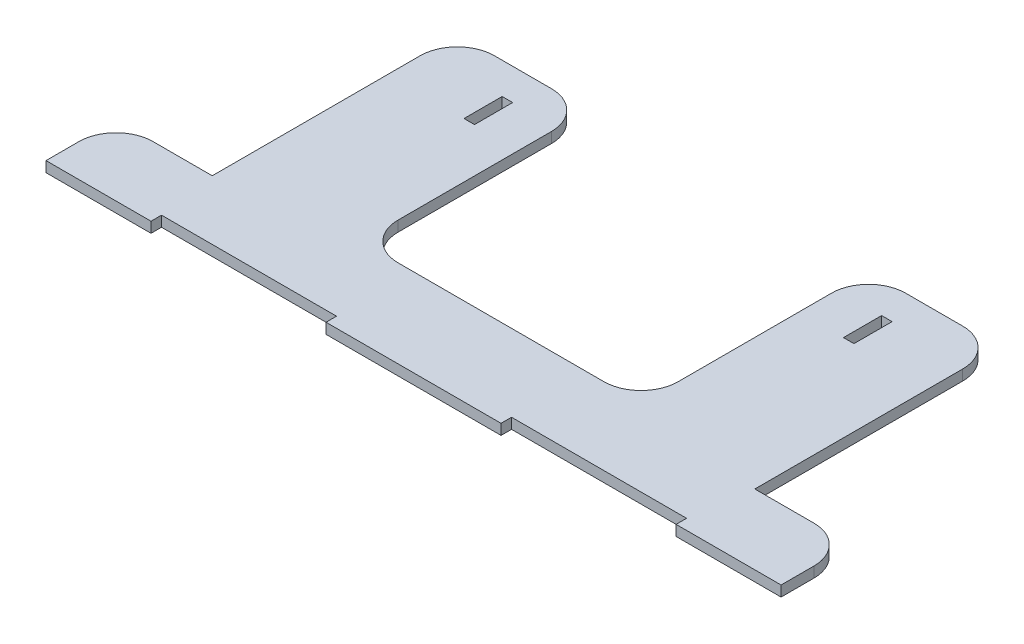
SolidWorks part; units mm, degrees
material "3mm Birch Ply Wood"
ref_plane "Front Plane" through (0, 0, 0) normal (0, 0, 1) x (1, 0, 0)
ref_plane "Top Plane" through (0, 0, 0) normal (0, 1, 0) x (1, 0, 0)
ref_plane "Right Plane" through (0, 0, 0) normal (1, 0, 0) x (0, 0, -1)
sketch "Sketch1" plane through (0, 0, 0) normal (0, 1, 0) x (1, 0, 0)
  line L35 (-50.3893, -230.7424) -> (-50.3893, -110.7424) construction
  line L37 (-155.3893, -110.7424) -> (-155.3893, -230.7424)
  line L38 (-155.3893, -230.7424) -> (54.6107, -230.7424)
  line L39 (54.6107, -110.7424) -> (54.6107, -230.7424)
  line L40 (54.6107, -110.7424) -> (-155.3893, -110.7424)
  point P62 (-50.3893, -110.7424)
extrude "Chasis Base" add sketch "Sketch1" along normal blind 3
sketch "Sketch7" plane through (0, 3, 0) normal (0, 1, 0) x (1, 0, 0)
  line L7 (-50.3893, -230.7424) -> (-50.3893, -80.7424) construction
  line L12 (-155.3893, -230.7424) -> (54.6107, -230.7424) construction
  line L15 (-75.3893, -230.7424) -> (-25.3893, -230.7424) construction
  line L16 (-155.3893, -230.7424) -> (-125.3893, -230.7424) construction
  line L17 (24.6107, -230.7424) -> (24.6107, -227.7424)
  line L18 (-25.3893, -227.7424) -> (24.6107, -227.7424)
  line L19 (-25.3893, -230.7424) -> (-25.3893, -227.7424)
  line L20 (-25.3893, -230.7424) -> (24.6107, -230.7424)
  line L21 (-75.3893, -230.7424) -> (-125.3893, -230.7424)
  line L22 (-75.3893, -227.7424) -> (-75.3893, -230.7424)
  line L23 (-125.3893, -227.7424) -> (-75.3893, -227.7424)
  line L24 (-125.3893, -230.7424) -> (-125.3893, -227.7424)
extrude "Front and Back Slots" cut sketch "Sketch7" against normal through all both and the other way through all
sketch "Sketch15" plane through (0, 3, 0) normal (0, 1, 0) x (1, 0, 0)
  line L0 (-50.3893, -230.7424) -> (-50.3893, -117.6525) construction
  line L6 (-75.3893, -230.7424) -> (-25.3893, -230.7424) construction
  line L7 (-155.3893, -175.7474) -> (-155.3893, -140.7474)
  line L22 (-155.3893, -140.7474) -> (-127.8893, -140.7474)
  line L23 (-127.8893, -140.7474) -> (-127.8893, -210.7474)
  line L24 (-127.8893, -210.7474) -> (-155.3893, -210.7474)
  line L25 (-155.3893, -175.7474) -> (-155.3893, -210.7474)
  line L26 (54.6107, -140.7474) -> (27.1107, -140.7474)
  line L27 (54.6107, -175.7474) -> (54.6107, -140.7474)
  line L28 (54.6107, -175.7474) -> (54.6107, -210.7474)
  line L29 (27.1107, -210.7474) -> (54.6107, -210.7474)
  line L30 (27.1107, -140.7474) -> (27.1107, -210.7474)
extrude "Back Wheels " cut sketch "Sketch15" against normal through all both and the other way through all
sketch "Sketch16" plane through (0, 3, 0) normal (0, 1, 0) x (1, 0, 0)
  line L1 (-106.0893, -149.7274) -> (-103.0893, -149.7274)
  line L2 (-106.0893, -149.7274) -> (-106.0893, -160.6274)
  line L3 (-106.0893, -160.6274) -> (-103.0893, -160.6274)
  line L4 (-103.0893, -149.7274) -> (-103.0893, -160.6274)
  line L5 (5.3107, -149.7274) -> (2.3107, -149.7274)
  line L6 (5.3107, -149.7274) -> (5.3107, -160.6274)
  line L7 (5.3107, -160.6274) -> (2.3107, -160.6274)
  line L8 (2.3107, -149.7274) -> (2.3107, -160.6274)
extrude "Cut-Extrude1" cut sketch "Sketch16" against normal through all both and the other way through all
sketch "Sketch17" plane through (0, 3, 0) normal (0, 1, 0) x (1, 0, 0)
  line L1 (-155.3893, -110.7424) -> (54.6107, -110.7424)
  line L2 (-155.3893, -110.7424) -> (-155.3893, -140.7474)
  line L3 (-155.3893, -140.7474) -> (54.6107, -140.7474)
  line L4 (54.6107, -110.7424) -> (54.6107, -140.7474)
extrude "Cut-Extrude2" cut sketch "Sketch17" against normal blind 10
sketch "Sketch18" plane through (0, 0, 0) normal (0, -1, 0) x (-1, 0, 0)
  line L0 (50.3893, -140.7474) -> (50.3893, -205.7474) construction
  line L1 (127.8893, -140.7474) -> (-27.1107, -140.7474) construction
  line L2 (10.3893, -140.7474) -> (10.3893, -205.7474)
  line L3 (90.3893, -140.7474) -> (90.3893, -205.7474)
  line L4 (90.3893, -205.7474) -> (10.3893, -205.7474)
  line L5 (90.3893, -140.7474) -> (10.3893, -140.7474)
  dimension "D1" = 40
  dimension "D2" = 40
extrude "Cut-Extrude3" cut sketch "Sketch18" against normal blind 57
sketch "Sketch19" plane through (0, 3, 0) normal (0, 1, 0) x (1, 0, 0)
  line L0 (-155.3893, -210.7474) -> (-144.7827, -221.354) construction
  line L1 (-155.3893, -221.354) -> (-155.3893, -210.7474)
  line L2 (-155.3893, -210.7474) -> (-144.7827, -210.7474)
  line L3 (-127.8893, -140.7474) -> (-117.2827, -140.7474)
  line L4 (-127.8893, -151.354) -> (-127.8893, -140.7474)
  line L5 (-127.8893, -140.7474) -> (-117.2827, -151.354) construction
  line L6 (-109.1393, -140.7474) -> (-109.1393, -169.844) construction
  line L7 (-127.8893, -140.7474) -> (-90.3893, -140.7474) construction
  line L8 (-90.3893, -140.7474) -> (-100.9959, -151.354) construction
  line L9 (-90.3893, -151.354) -> (-90.3893, -140.7474)
  line L10 (-90.3893, -140.7474) -> (-100.9959, -140.7474)
  line L11 (-50.3893, -205.7474) -> (-50.3893, -116.723) construction
  line L12 (-90.3893, -205.7474) -> (-10.3893, -205.7474) construction
  line L13 (-10.3893, -140.7474) -> (0.2173, -151.354) construction
  line L14 (8.3607, -140.7474) -> (8.3607, -169.844) construction
  line L15 (27.1107, -140.7474) -> (16.5041, -151.354) construction
  line L16 (54.6107, -210.7474) -> (44.0041, -221.354) construction
  line L17 (-10.3893, -140.7474) -> (0.2173, -140.7474)
  line L18 (-10.3893, -151.354) -> (-10.3893, -140.7474)
  line L19 (27.1107, -151.354) -> (27.1107, -140.7474)
  line L20 (27.1107, -140.7474) -> (16.5041, -140.7474)
  line L21 (54.6107, -210.7474) -> (44.0041, -210.7474)
  line L22 (54.6107, -221.354) -> (54.6107, -210.7474)
  arc A0 (-144.7827, -210.7474) -> (-155.3893, -221.354) centre (-144.7827, -221.354) ccw
  arc A1 (-117.2827, -140.7474) -> (-127.8893, -151.354) centre (-117.2827, -151.354) ccw
  arc A2 (-100.9959, -140.7474) -> (-90.3893, -151.354) centre (-100.9959, -151.354) cw
  arc A3 (0.2173, -140.7474) -> (-10.3893, -151.354) centre (0.2173, -151.354) ccw
  arc A4 (16.5041, -140.7474) -> (27.1107, -151.354) centre (16.5041, -151.354) cw
  arc A5 (44.0041, -210.7474) -> (54.6107, -221.354) centre (44.0041, -221.354) cw
extrude "Cut-Extrude4" cut sketch "Sketch19" against normal blind 10
sketch "Sketch20" plane through (0, 0, 0) normal (0, 1, 0) x (1, 0, 0)
  line L0 (-90.3893, -205.7474) -> (-79.7827, -195.1408) construction
  line L1 (-90.3893, -195.1408) -> (-90.3893, -205.7474)
  line L2 (-90.3893, -205.7474) -> (-79.7827, -205.7474)
  line L3 (-50.3893, -205.7474) -> (-50.3893, -222.8379) construction
  line L4 (-90.3893, -205.7474) -> (-10.3893, -205.7474) construction
  line L5 (-10.3893, -205.7474) -> (-20.9959, -195.1408) construction
  line L6 (-10.3893, -205.7474) -> (-20.9959, -205.7474)
  line L7 (-10.3893, -195.1408) -> (-10.3893, -205.7474)
  arc A0 (-90.3893, -195.1408) -> (-79.7827, -205.7474) centre (-79.7827, -195.1408) ccw
  arc A1 (-10.3893, -195.1408) -> (-20.9959, -205.7474) centre (-20.9959, -195.1408) cw
extrude "Boss-Extrude1" add sketch "Sketch20" along normal blind 3
